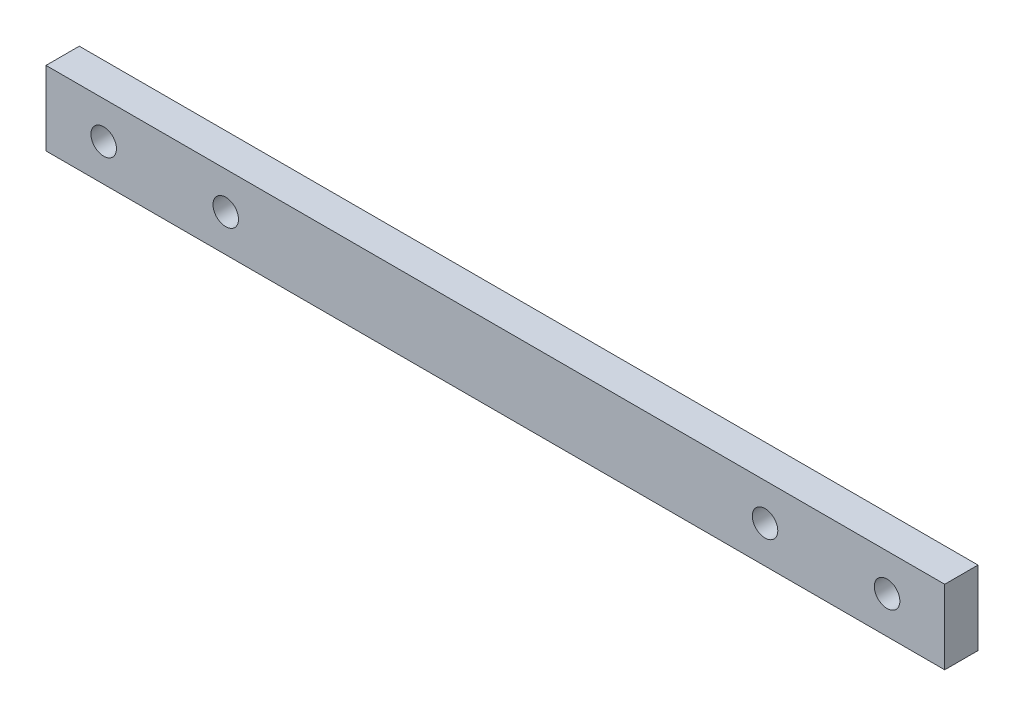
SolidWorks part; units mm, degrees
ref_plane "前视基准面" through (0, 0, 0) normal (0, 0, 1) x (1, 0, 0)
ref_plane "上视基准面" through (0, 0, 0) normal (0, 1, 0) x (1, 0, 0)
ref_plane "右视基准面" through (0, 0, 0) normal (1, 0, 0) x (0, 0, -1)
sketch "草图1" plane through (0, 0, 0) normal (0, 0, 1) x (1, 0, 0)
  line L0 (-40.497, -10.59) -> (40.497, -10.59)
  line L6 (40.497, -10.59) -> (40.497, -17.27)
  line L7 (40.497, -17.27) -> (-40.497, -17.27)
  line L8 (-40.497, -17.27) -> (-40.497, -10.59)
  line L10 (-35.297, -13.93) -> (-24.297, -13.93) construction
  line L11 (-24.297, -13.93) -> (24.303, -13.93) construction
  line L12 (24.303, -13.93) -> (35.303, -13.93) construction
  line L13 (35.303, -13.93) -> (35.303, -10.59) construction
  line L14 (35.303, -13.93) -> (35.303, -17.27) construction
  circle A0 centre (-35.297, -13.93) radius 1.15
  circle A1 centre (-24.297, -13.93) radius 1.15
  circle A2 centre (24.303, -13.93) radius 1.15
  circle A3 centre (35.303, -13.93) radius 1.15
  dimension "D1" = 48.6
  dimension "D2" = 11
  dimension "D5" = 6.68
extrude "凸台-拉伸1" add sketch "草图1" along normal blind 3
